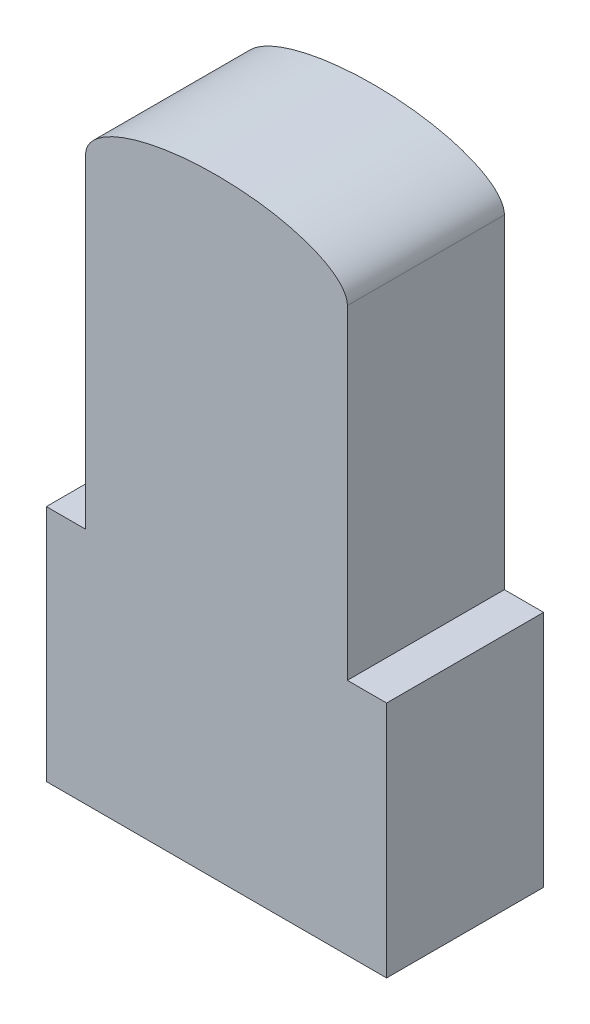
SolidWorks part; units mm, degrees
ref_plane "Alzado" through (0, 0, 0) normal (0, 0, 1) x (1, 0, 0)
ref_plane "Planta" through (0, 0, 0) normal (0, 1, 0) x (1, 0, 0)
ref_plane "Vista lateral" through (0, 0, 0) normal (1, 0, 0) x (0, 0, -1)
sketch "Model" plane through (0, 0, 0) normal (0, 0, 1) x (1, 0, 0)
  line L0 (10.7973, 296.5179) -> (10.7973, 290.3179)
  line L1 (15.7973, 290.3179) -> (15.7973, 296.5179)
  line L2 (10.7973, 290.3179) -> (10.0473, 290.3179)
  line L3 (10.0473, 290.3179) -> (10.0473, 285.7679)
  line L4 (10.0473, 285.7679) -> (16.5473, 285.7679)
  line L5 (16.5473, 285.7679) -> (16.5473, 290.3179)
  line L6 (16.5473, 290.3179) -> (15.7973, 290.3179)
  ellipse E0 centre (13.2973, 296.5179) end of major axis (15.7973, 296.5179) minor radius 0.9095 (15.7973, 296.5179) -> (10.7973, 296.5179) ccw
extrude "Saliente-Extruir1" add sketch "Model" along normal blind 3
